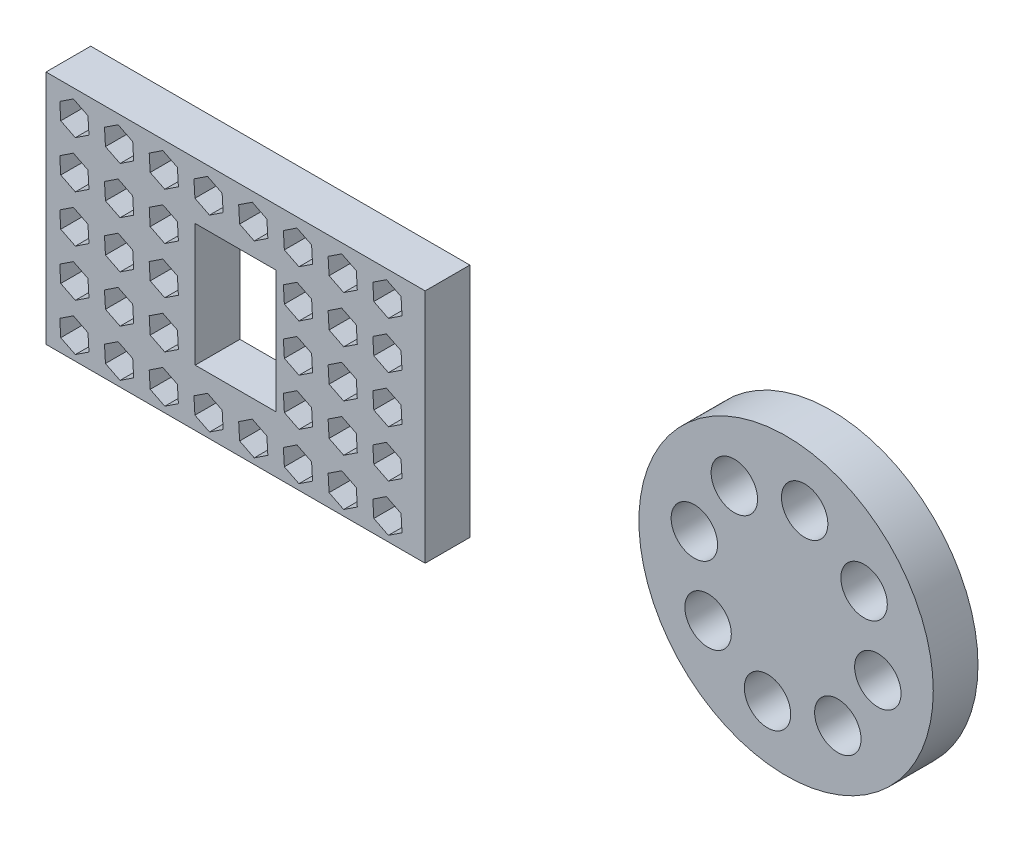
SolidWorks part; units mm, degrees
ref_plane "Front Plane" through (0, 0, 0) normal (0, 0, 1) x (1, 0, 0)
ref_plane "Top Plane" through (0, 0, 0) normal (0, 1, 0) x (1, 0, 0)
ref_plane "Right Plane" through (0, 0, 0) normal (1, 0, 0) x (0, 0, -1)
sketch "Sketch1" plane through (0, 0, 0) normal (0, 0, 1) x (1, 0, 0)
  line L0 (-22.7839, -23.0572) -> (-23.0026, -19.4148)
  line L1 (-42.3867, -26.3718) -> (42.3867, -26.3718)
  line L2 (-42.3867, -26.3718) -> (-42.3867, 26.3718)
  line L3 (-42.3867, 26.3718) -> (42.3867, 26.3718)
  line L4 (42.3867, -26.3718) -> (42.3867, 26.3718)
  line L5 (-42.3867, -26.3718) -> (42.3867, 26.3718) construction
  line L6 (-42.3867, 26.3718) -> (42.3867, -26.3718) construction
  line L7 (-32.7839, -23.0572) -> (-33.0026, -19.4148)
  line L8 (-33.0026, -19.4148) -> (-36.2663, -17.783)
  line L9 (-36.2663, -17.783) -> (-39.3113, -19.7935)
  line L10 (-39.3113, -19.7935) -> (-39.0927, -23.4359)
  line L11 (-39.0927, -23.4359) -> (-35.829, -25.0677)
  line L12 (-35.829, -25.0677) -> (-32.7839, -23.0572)
  line L13 (-23.0026, -19.4148) -> (-26.2663, -17.783)
  line L14 (-26.2663, -17.783) -> (-29.3113, -19.7935)
  line L15 (-29.3113, -19.7935) -> (-29.0927, -23.4359)
  line L16 (-29.0927, -23.4359) -> (-25.829, -25.0677)
  line L17 (-25.829, -25.0677) -> (-22.7839, -23.0572)
  line L18 (-32.3867, -26.3718) -> (52.3867, 26.3718) construction
  line L19 (-12.7839, -23.0572) -> (-13.0026, -19.4148)
  line L20 (-13.0026, -19.4148) -> (-16.2663, -17.783)
  line L21 (-16.2663, -17.783) -> (-19.3113, -19.7935)
  line L22 (-19.3113, -19.7935) -> (-19.0927, -23.4359)
  line L23 (-19.0927, -23.4359) -> (-15.829, -25.0677)
  line L24 (-15.829, -25.0677) -> (-12.7839, -23.0572)
  line L25 (-22.3867, -26.3718) -> (62.3867, 26.3718) construction
  line L26 (-2.7839, -23.0572) -> (-3.0026, -19.4148)
  line L27 (-3.0026, -19.4148) -> (-6.2663, -17.783)
  line L28 (-6.2663, -17.783) -> (-9.3113, -19.7935)
  line L29 (-9.3113, -19.7935) -> (-9.0927, -23.4359)
  line L30 (-9.0927, -23.4359) -> (-5.829, -25.0677)
  line L31 (-5.829, -25.0677) -> (-2.7839, -23.0572)
  line L32 (-12.3867, -26.3718) -> (72.3867, 26.3718) construction
  line L33 (7.2161, -23.0572) -> (6.9974, -19.4148)
  line L34 (6.9974, -19.4148) -> (3.7337, -17.783)
  line L35 (3.7337, -17.783) -> (0.6887, -19.7935)
  line L36 (0.6887, -19.7935) -> (0.9073, -23.4359)
  line L37 (0.9073, -23.4359) -> (4.171, -25.0677)
  line L38 (4.171, -25.0677) -> (7.2161, -23.0572)
  line L39 (-2.3867, -26.3718) -> (82.3867, 26.3718) construction
  line L40 (17.2161, -23.0572) -> (16.9974, -19.4148)
  line L41 (16.9974, -19.4148) -> (13.7337, -17.783)
  line L42 (13.7337, -17.783) -> (10.6887, -19.7935)
  line L43 (10.6887, -19.7935) -> (10.9073, -23.4359)
  line L44 (10.9073, -23.4359) -> (14.171, -25.0677)
  line L45 (14.171, -25.0677) -> (17.2161, -23.0572)
  line L46 (7.6133, -26.3718) -> (92.3867, 26.3718) construction
  line L47 (27.2161, -23.0572) -> (26.9974, -19.4148)
  line L48 (26.9974, -19.4148) -> (23.7337, -17.783)
  line L49 (23.7337, -17.783) -> (20.6887, -19.7935)
  line L50 (20.6887, -19.7935) -> (20.9073, -23.4359)
  line L51 (20.9073, -23.4359) -> (24.171, -25.0677)
  line L52 (24.171, -25.0677) -> (27.2161, -23.0572)
  line L53 (17.6133, -26.3718) -> (102.3867, 26.3718) construction
  line L54 (37.2161, -23.0572) -> (36.9974, -19.4148)
  line L55 (36.9974, -19.4148) -> (33.7337, -17.783)
  line L56 (33.7337, -17.783) -> (30.6887, -19.7935)
  line L57 (30.6887, -19.7935) -> (30.9073, -23.4359)
  line L58 (30.9073, -23.4359) -> (34.171, -25.0677)
  line L59 (34.171, -25.0677) -> (37.2161, -23.0572)
  line L60 (27.6133, -26.3718) -> (112.3867, 26.3718) construction
  line L61 (-22.7839, -12.5572) -> (-23.0026, -8.9148)
  line L62 (-23.0026, -8.9148) -> (-26.2663, -7.283)
  line L63 (-26.2663, -7.283) -> (-29.3113, -9.2935)
  line L64 (-29.3113, -9.2935) -> (-29.0927, -12.9359)
  line L65 (-29.0927, -12.9359) -> (-25.829, -14.5677)
  line L66 (-25.829, -14.5677) -> (-22.7839, -12.5572)
  line L67 (-32.3867, -15.8718) -> (52.3867, 36.8718) construction
  line L68 (-12.7839, -12.5572) -> (-13.0026, -8.9148)
  line L69 (-13.0026, -8.9148) -> (-16.2663, -7.283)
  line L70 (-16.2663, -7.283) -> (-19.3113, -9.2935)
  line L71 (-19.3113, -9.2935) -> (-19.0927, -12.9359)
  line L72 (-19.0927, -12.9359) -> (-15.829, -14.5677)
  line L73 (-15.829, -14.5677) -> (-12.7839, -12.5572)
  line L74 (-22.3867, -15.8718) -> (62.3867, 36.8718) construction
  line L75 (-2.7839, -12.5572) -> (-3.0026, -8.9148) [skipped]
  line L76 (-3.0026, -8.9148) -> (-6.2663, -7.283) [skipped]
  line L77 (-6.2663, -7.283) -> (-9.3113, -9.2935) [skipped]
  line L78 (-9.3113, -9.2935) -> (-9.0927, -12.9359) [skipped]
  line L79 (-9.0927, -12.9359) -> (-5.829, -14.5677) [skipped]
  line L80 (-5.829, -14.5677) -> (-2.7839, -12.5572) [skipped]
  line L81 (-12.3867, -15.8718) -> (72.3867, 36.8718) construction
  line L82 (7.2161, -12.5572) -> (6.9974, -8.9148) [skipped]
  line L83 (6.9974, -8.9148) -> (3.7337, -7.283) [skipped]
  line L84 (3.7337, -7.283) -> (0.6887, -9.2935) [skipped]
  line L85 (0.6887, -9.2935) -> (0.9073, -12.9359) [skipped]
  line L86 (0.9073, -12.9359) -> (4.171, -14.5677) [skipped]
  line L87 (4.171, -14.5677) -> (7.2161, -12.5572) [skipped]
  line L88 (-2.3867, -15.8718) -> (82.3867, 36.8718) construction
  line L89 (17.2161, -12.5572) -> (16.9974, -8.9148)
  line L90 (16.9974, -8.9148) -> (13.7337, -7.283)
  line L91 (13.7337, -7.283) -> (10.6887, -9.2935)
  line L92 (10.6887, -9.2935) -> (10.9073, -12.9359)
  line L93 (10.9073, -12.9359) -> (14.171, -14.5677)
  line L94 (14.171, -14.5677) -> (17.2161, -12.5572)
  line L95 (7.6133, -15.8718) -> (92.3867, 36.8718) construction
  line L96 (27.2161, -12.5572) -> (26.9974, -8.9148)
  line L97 (26.9974, -8.9148) -> (23.7337, -7.283)
  line L98 (23.7337, -7.283) -> (20.6887, -9.2935)
  line L99 (20.6887, -9.2935) -> (20.9073, -12.9359)
  line L100 (20.9073, -12.9359) -> (24.171, -14.5677)
  line L101 (24.171, -14.5677) -> (27.2161, -12.5572)
  line L102 (17.6133, -15.8718) -> (102.3867, 36.8718) construction
  line L103 (37.2161, -12.5572) -> (36.9974, -8.9148)
  line L104 (36.9974, -8.9148) -> (33.7337, -7.283)
  line L105 (33.7337, -7.283) -> (30.6887, -9.2935)
  line L106 (30.6887, -9.2935) -> (30.9073, -12.9359)
  line L107 (30.9073, -12.9359) -> (34.171, -14.5677)
  line L108 (34.171, -14.5677) -> (37.2161, -12.5572)
  line L109 (27.6133, -15.8718) -> (112.3867, 36.8718) construction
  line L110 (-22.7839, -2.0572) -> (-23.0026, 1.5852)
  line L111 (-23.0026, 1.5852) -> (-26.2663, 3.217)
  line L112 (-26.2663, 3.217) -> (-29.3113, 1.2065)
  line L113 (-29.3113, 1.2065) -> (-29.0927, -2.4359)
  line L114 (-29.0927, -2.4359) -> (-25.829, -4.0677)
  line L115 (-25.829, -4.0677) -> (-22.7839, -2.0572)
  line L116 (-32.3867, -5.3718) -> (52.3867, 47.3718) construction
  line L117 (-12.7839, -2.0572) -> (-13.0026, 1.5852)
  line L118 (-13.0026, 1.5852) -> (-16.2663, 3.217)
  line L119 (-16.2663, 3.217) -> (-19.3113, 1.2065)
  line L120 (-19.3113, 1.2065) -> (-19.0927, -2.4359)
  line L121 (-19.0927, -2.4359) -> (-15.829, -4.0677)
  line L122 (-15.829, -4.0677) -> (-12.7839, -2.0572)
  line L123 (-22.3867, -5.3718) -> (62.3867, 47.3718) construction
  line L124 (-2.7839, -2.0572) -> (-3.0026, 1.5852) [skipped]
  line L125 (-3.0026, 1.5852) -> (-6.2663, 3.217) [skipped]
  line L126 (-6.2663, 3.217) -> (-9.3113, 1.2065) [skipped]
  line L127 (-9.3113, 1.2065) -> (-9.0927, -2.4359) [skipped]
  line L128 (-9.0927, -2.4359) -> (-5.829, -4.0677) [skipped]
  line L129 (-5.829, -4.0677) -> (-2.7839, -2.0572) [skipped]
  line L130 (-12.3867, -5.3718) -> (72.3867, 47.3718) construction
  line L131 (7.2161, -2.0572) -> (6.9974, 1.5852) [skipped]
  line L132 (6.9974, 1.5852) -> (3.7337, 3.217) [skipped]
  line L133 (3.7337, 3.217) -> (0.6887, 1.2065) [skipped]
  line L134 (0.6887, 1.2065) -> (0.9073, -2.4359) [skipped]
  line L135 (0.9073, -2.4359) -> (4.171, -4.0677) [skipped]
  line L136 (4.171, -4.0677) -> (7.2161, -2.0572) [skipped]
  line L137 (-2.3867, -5.3718) -> (82.3867, 47.3718) construction
  line L138 (17.2161, -2.0572) -> (16.9974, 1.5852)
  line L139 (16.9974, 1.5852) -> (13.7337, 3.217)
  line L140 (13.7337, 3.217) -> (10.6887, 1.2065)
  line L141 (10.6887, 1.2065) -> (10.9073, -2.4359)
  line L142 (10.9073, -2.4359) -> (14.171, -4.0677)
  line L143 (14.171, -4.0677) -> (17.2161, -2.0572)
  line L144 (7.6133, -5.3718) -> (92.3867, 47.3718) construction
  line L145 (27.2161, -2.0572) -> (26.9974, 1.5852)
  line L146 (26.9974, 1.5852) -> (23.7337, 3.217)
  line L147 (23.7337, 3.217) -> (20.6887, 1.2065)
  line L148 (20.6887, 1.2065) -> (20.9073, -2.4359)
  line L149 (20.9073, -2.4359) -> (24.171, -4.0677)
  line L150 (24.171, -4.0677) -> (27.2161, -2.0572)
  line L151 (17.6133, -5.3718) -> (102.3867, 47.3718) construction
  line L152 (37.2161, -2.0572) -> (36.9974, 1.5852)
  line L153 (36.9974, 1.5852) -> (33.7337, 3.217)
  line L154 (33.7337, 3.217) -> (30.6887, 1.2065)
  line L155 (30.6887, 1.2065) -> (30.9073, -2.4359)
  line L156 (30.9073, -2.4359) -> (34.171, -4.0677)
  line L157 (34.171, -4.0677) -> (37.2161, -2.0572)
  line L158 (27.6133, -5.3718) -> (112.3867, 47.3718) construction
  line L159 (-22.7839, 8.4428) -> (-23.0026, 12.0852)
  line L160 (-23.0026, 12.0852) -> (-26.2663, 13.717)
  line L161 (-26.2663, 13.717) -> (-29.3113, 11.7065)
  line L162 (-29.3113, 11.7065) -> (-29.0927, 8.0641)
  line L163 (-29.0927, 8.0641) -> (-25.829, 6.4323)
  line L164 (-25.829, 6.4323) -> (-22.7839, 8.4428)
  line L165 (-32.3867, 5.1282) -> (52.3867, 57.8718) construction
  line L166 (-12.7839, 8.4428) -> (-13.0026, 12.0852)
  line L167 (-13.0026, 12.0852) -> (-16.2663, 13.717)
  line L168 (-16.2663, 13.717) -> (-19.3113, 11.7065)
  line L169 (-19.3113, 11.7065) -> (-19.0927, 8.0641)
  line L170 (-19.0927, 8.0641) -> (-15.829, 6.4323)
  line L171 (-15.829, 6.4323) -> (-12.7839, 8.4428)
  line L172 (-22.3867, 5.1282) -> (62.3867, 57.8718) construction
  line L173 (-2.7839, 8.4428) -> (-3.0026, 12.0852) [skipped]
  line L174 (-3.0026, 12.0852) -> (-6.2663, 13.717) [skipped]
  line L175 (-6.2663, 13.717) -> (-9.3113, 11.7065) [skipped]
  line L176 (-9.3113, 11.7065) -> (-9.0927, 8.0641) [skipped]
  line L177 (-9.0927, 8.0641) -> (-5.829, 6.4323) [skipped]
  line L178 (-5.829, 6.4323) -> (-2.7839, 8.4428) [skipped]
  line L179 (-12.3867, 5.1282) -> (72.3867, 57.8718) construction
  line L180 (7.2161, 8.4428) -> (6.9974, 12.0852) [skipped]
  line L181 (6.9974, 12.0852) -> (3.7337, 13.717) [skipped]
  line L182 (3.7337, 13.717) -> (0.6887, 11.7065) [skipped]
  line L183 (0.6887, 11.7065) -> (0.9073, 8.0641) [skipped]
  line L184 (0.9073, 8.0641) -> (4.171, 6.4323) [skipped]
  line L185 (4.171, 6.4323) -> (7.2161, 8.4428) [skipped]
  line L186 (-2.3867, 5.1282) -> (82.3867, 57.8718) construction
  line L187 (17.2161, 8.4428) -> (16.9974, 12.0852)
  line L188 (16.9974, 12.0852) -> (13.7337, 13.717)
  line L189 (13.7337, 13.717) -> (10.6887, 11.7065)
  line L190 (10.6887, 11.7065) -> (10.9073, 8.0641)
  line L191 (10.9073, 8.0641) -> (14.171, 6.4323)
  line L192 (14.171, 6.4323) -> (17.2161, 8.4428)
  line L193 (7.6133, 5.1282) -> (92.3867, 57.8718) construction
  line L194 (27.2161, 8.4428) -> (26.9974, 12.0852)
  line L195 (26.9974, 12.0852) -> (23.7337, 13.717)
  line L196 (23.7337, 13.717) -> (20.6887, 11.7065)
  line L197 (20.6887, 11.7065) -> (20.9073, 8.0641)
  line L198 (20.9073, 8.0641) -> (24.171, 6.4323)
  line L199 (24.171, 6.4323) -> (27.2161, 8.4428)
  line L200 (17.6133, 5.1282) -> (102.3867, 57.8718) construction
  line L201 (37.2161, 8.4428) -> (36.9974, 12.0852)
  line L202 (36.9974, 12.0852) -> (33.7337, 13.717)
  line L203 (33.7337, 13.717) -> (30.6887, 11.7065)
  line L204 (30.6887, 11.7065) -> (30.9073, 8.0641)
  line L205 (30.9073, 8.0641) -> (34.171, 6.4323)
  line L206 (34.171, 6.4323) -> (37.2161, 8.4428)
  line L207 (27.6133, 5.1282) -> (112.3867, 57.8718) construction
  line L208 (-22.7839, 18.9428) -> (-23.0026, 22.5852)
  line L209 (-23.0026, 22.5852) -> (-26.2663, 24.217)
  line L210 (-26.2663, 24.217) -> (-29.3113, 22.2065)
  line L211 (-29.3113, 22.2065) -> (-29.0927, 18.5641)
  line L212 (-29.0927, 18.5641) -> (-25.829, 16.9323)
  line L213 (-25.829, 16.9323) -> (-22.7839, 18.9428)
  line L214 (-32.3867, 15.6282) -> (52.3867, 68.3718) construction
  line L215 (-12.7839, 18.9428) -> (-13.0026, 22.5852)
  line L216 (-13.0026, 22.5852) -> (-16.2663, 24.217)
  line L217 (-16.2663, 24.217) -> (-19.3113, 22.2065)
  line L218 (-19.3113, 22.2065) -> (-19.0927, 18.5641)
  line L219 (-19.0927, 18.5641) -> (-15.829, 16.9323)
  line L220 (-15.829, 16.9323) -> (-12.7839, 18.9428)
  line L221 (-22.3867, 15.6282) -> (62.3867, 68.3718) construction
  line L222 (-2.7839, 18.9428) -> (-3.0026, 22.5852)
  line L223 (-3.0026, 22.5852) -> (-6.2663, 24.217)
  line L224 (-6.2663, 24.217) -> (-9.3113, 22.2065)
  line L225 (-9.3113, 22.2065) -> (-9.0927, 18.5641)
  line L226 (-9.0927, 18.5641) -> (-5.829, 16.9323)
  line L227 (-5.829, 16.9323) -> (-2.7839, 18.9428)
  line L228 (-12.3867, 15.6282) -> (72.3867, 68.3718) construction
  line L229 (7.2161, 18.9428) -> (6.9974, 22.5852)
  line L230 (6.9974, 22.5852) -> (3.7337, 24.217)
  line L231 (3.7337, 24.217) -> (0.6887, 22.2065)
  line L232 (0.6887, 22.2065) -> (0.9073, 18.5641)
  line L233 (0.9073, 18.5641) -> (4.171, 16.9323)
  line L234 (4.171, 16.9323) -> (7.2161, 18.9428)
  line L235 (-2.3867, 15.6282) -> (82.3867, 68.3718) construction
  line L236 (17.2161, 18.9428) -> (16.9974, 22.5852)
  line L237 (16.9974, 22.5852) -> (13.7337, 24.217)
  line L238 (13.7337, 24.217) -> (10.6887, 22.2065)
  line L239 (10.6887, 22.2065) -> (10.9073, 18.5641)
  line L240 (10.9073, 18.5641) -> (14.171, 16.9323)
  line L241 (14.171, 16.9323) -> (17.2161, 18.9428)
  line L242 (7.6133, 15.6282) -> (92.3867, 68.3718) construction
  line L243 (27.2161, 18.9428) -> (26.9974, 22.5852)
  line L244 (26.9974, 22.5852) -> (23.7337, 24.217)
  line L245 (23.7337, 24.217) -> (20.6887, 22.2065)
  line L246 (20.6887, 22.2065) -> (20.9073, 18.5641)
  line L247 (20.9073, 18.5641) -> (24.171, 16.9323)
  line L248 (24.171, 16.9323) -> (27.2161, 18.9428)
  line L249 (17.6133, 15.6282) -> (102.3867, 68.3718) construction
  line L250 (37.2161, 18.9428) -> (36.9974, 22.5852)
  line L251 (36.9974, 22.5852) -> (33.7337, 24.217)
  line L252 (33.7337, 24.217) -> (30.6887, 22.2065)
  line L253 (30.6887, 22.2065) -> (30.9073, 18.5641)
  line L254 (30.9073, 18.5641) -> (34.171, 16.9323)
  line L255 (34.171, 16.9323) -> (37.2161, 18.9428)
  line L256 (27.6133, 15.6282) -> (112.3867, 68.3718) construction
  line L257 (-32.7839, -12.5572) -> (-33.0026, -8.9148)
  line L258 (-33.0026, -8.9148) -> (-36.2663, -7.283)
  line L259 (-36.2663, -7.283) -> (-39.3113, -9.2935)
  line L260 (-39.3113, -9.2935) -> (-39.0927, -12.9359)
  line L261 (-39.0927, -12.9359) -> (-35.829, -14.5677)
  line L262 (-35.829, -14.5677) -> (-32.7839, -12.5572)
  line L263 (-42.3867, -15.8718) -> (42.3867, 36.8718) construction
  line L264 (-32.7839, -2.0572) -> (-33.0026, 1.5852)
  line L265 (-33.0026, 1.5852) -> (-36.2663, 3.217)
  line L266 (-36.2663, 3.217) -> (-39.3113, 1.2065)
  line L267 (-39.3113, 1.2065) -> (-39.0927, -2.4359)
  line L268 (-39.0927, -2.4359) -> (-35.829, -4.0677)
  line L269 (-35.829, -4.0677) -> (-32.7839, -2.0572)
  line L270 (-42.3867, -5.3718) -> (42.3867, 47.3718) construction
  line L271 (-32.7839, 8.4428) -> (-33.0026, 12.0852)
  line L272 (-33.0026, 12.0852) -> (-36.2663, 13.717)
  line L273 (-36.2663, 13.717) -> (-39.3113, 11.7065)
  line L274 (-39.3113, 11.7065) -> (-39.0927, 8.0641)
  line L275 (-39.0927, 8.0641) -> (-35.829, 6.4323)
  line L276 (-35.829, 6.4323) -> (-32.7839, 8.4428)
  line L277 (-42.3867, 5.1282) -> (42.3867, 57.8718) construction
  line L278 (-32.7839, 18.9428) -> (-33.0026, 22.5852)
  line L279 (-33.0026, 22.5852) -> (-36.2663, 24.217)
  line L280 (-36.2663, 24.217) -> (-39.3113, 22.2065)
  line L281 (-39.3113, 22.2065) -> (-39.0927, 18.5641)
  line L282 (-39.0927, 18.5641) -> (-35.829, 16.9323)
  line L283 (-35.829, 16.9323) -> (-32.7839, 18.9428)
  line L284 (-42.3867, 15.6282) -> (42.3867, 68.3718) construction
  line L286 (-9.0261, -13.717) -> (9.0261, -13.717)
  line L287 (-9.0261, -13.717) -> (-9.0261, 13.717)
  line L288 (-9.0261, 13.717) -> (9.0261, 13.717)
  line L289 (9.0261, -13.717) -> (9.0261, 13.717)
  line L290 (-9.0261, -13.717) -> (9.0261, 13.717) construction
  line L291 (-9.0261, 13.717) -> (9.0261, -13.717) construction
  circle A0 centre (-36.0476, -21.4254) radius 3.1601 construction
  circle A1 centre (-26.0476, -21.4254) radius 3.1601 construction
  circle A2 centre (-16.0476, -21.4254) radius 3.1601 construction
  circle A3 centre (-6.0476, -21.4254) radius 3.1601 construction
  circle A4 centre (3.9524, -21.4254) radius 3.1601 construction
  circle A5 centre (13.9524, -21.4254) radius 3.1601 construction
  circle A6 centre (23.9524, -21.4254) radius 3.1601 construction
  circle A7 centre (33.9524, -21.4254) radius 3.1601 construction
  circle A8 centre (-26.0476, -10.9254) radius 3.1601 construction
  circle A9 centre (-16.0476, -10.9254) radius 3.1601 construction
  circle A10 centre (-6.0476, -10.9254) radius 3.1601 construction
  circle A11 centre (3.9524, -10.9254) radius 3.1601 construction
  circle A12 centre (13.9524, -10.9254) radius 3.1601 construction
  circle A13 centre (23.9524, -10.9254) radius 3.1601 construction
  circle A14 centre (33.9524, -10.9254) radius 3.1601 construction
  circle A15 centre (-26.0476, -0.4254) radius 3.1601 construction
  circle A16 centre (-16.0476, -0.4254) radius 3.1601 construction
  circle A17 centre (-6.0476, -0.4254) radius 3.1601 construction
  circle A18 centre (3.9524, -0.4254) radius 3.1601 construction
  circle A19 centre (13.9524, -0.4254) radius 3.1601 construction
  circle A20 centre (23.9524, -0.4254) radius 3.1601 construction
  circle A21 centre (33.9524, -0.4254) radius 3.1601 construction
  circle A22 centre (-26.0476, 10.0746) radius 3.1601 construction
  circle A23 centre (-16.0476, 10.0746) radius 3.1601 construction
  circle A24 centre (-6.0476, 10.0746) radius 3.1601 construction
  circle A25 centre (3.9524, 10.0746) radius 3.1601 construction
  circle A26 centre (13.9524, 10.0746) radius 3.1601 construction
  circle A27 centre (23.9524, 10.0746) radius 3.1601 construction
  circle A28 centre (33.9524, 10.0746) radius 3.1601 construction
  circle A29 centre (-26.0476, 20.5746) radius 3.1601 construction
  circle A30 centre (-16.0476, 20.5746) radius 3.1601 construction
  circle A31 centre (-6.0476, 20.5746) radius 3.1601 construction
  circle A32 centre (3.9524, 20.5746) radius 3.1601 construction
  circle A33 centre (13.9524, 20.5746) radius 3.1601 construction
  circle A34 centre (23.9524, 20.5746) radius 3.1601 construction
  circle A35 centre (33.9524, 20.5746) radius 3.1601 construction
  circle A36 centre (-36.0476, -10.9254) radius 3.1601 construction
  circle A37 centre (-36.0476, -0.4254) radius 3.1601 construction
  circle A38 centre (-36.0476, 10.0746) radius 3.1601 construction
  circle A39 centre (-36.0476, 20.5746) radius 3.1601 construction
  circle A40 centre (123.09, 5.7353) radius 32.9094
  circle A41 centre (143.602, 1.5852) radius 5.19
  circle A42 centre (134.6595, -11.7034) radius 5.19
  circle A43 centre (118.9398, -14.7766) radius 5.19
  circle A44 centre (105.6512, -5.8342) radius 5.19
  circle A45 centre (102.578, 9.8855) radius 5.19
  circle A46 centre (111.5204, 23.1741) radius 5.19
  circle A47 centre (127.2402, 26.2473) radius 5.19
  circle A48 centre (140.5288, 17.3049) radius 5.19
  point P0 (0, 0)
  point P7 (0, 0)
  point P413 (117.962, -2.0572)
  point P414 (107.9759, 1.5852)
  point P415 (31.9967, 88.7176)
  point P418 (117.3546, 128.8253)
  point P421 (206.0722, 96.8286)
  point P424 (246.18, 11.4707)
  point P427 (214.1832, -77.2469)
  point P430 (128.8253, -117.3546)
  point P433 (40.1077, -85.3579)
  point P436 (123.09, 5.7353)
  point P437 (0, 0)
  point P438 (0, 0)
  point P439 (0, 0)
  point P440 (0, 0)
  point P441 (0, 0)
  point P442 (0, 0)
  point P443 (123.09, 5.7353)
  point P444 (143.602, 1.5852)
  dimension "D1" = 8
  dimension "D2" = 5
  dimension "D3" = 8
extrude "Boss-Extrude1" add sketch "Sketch1" along normal blind 10
